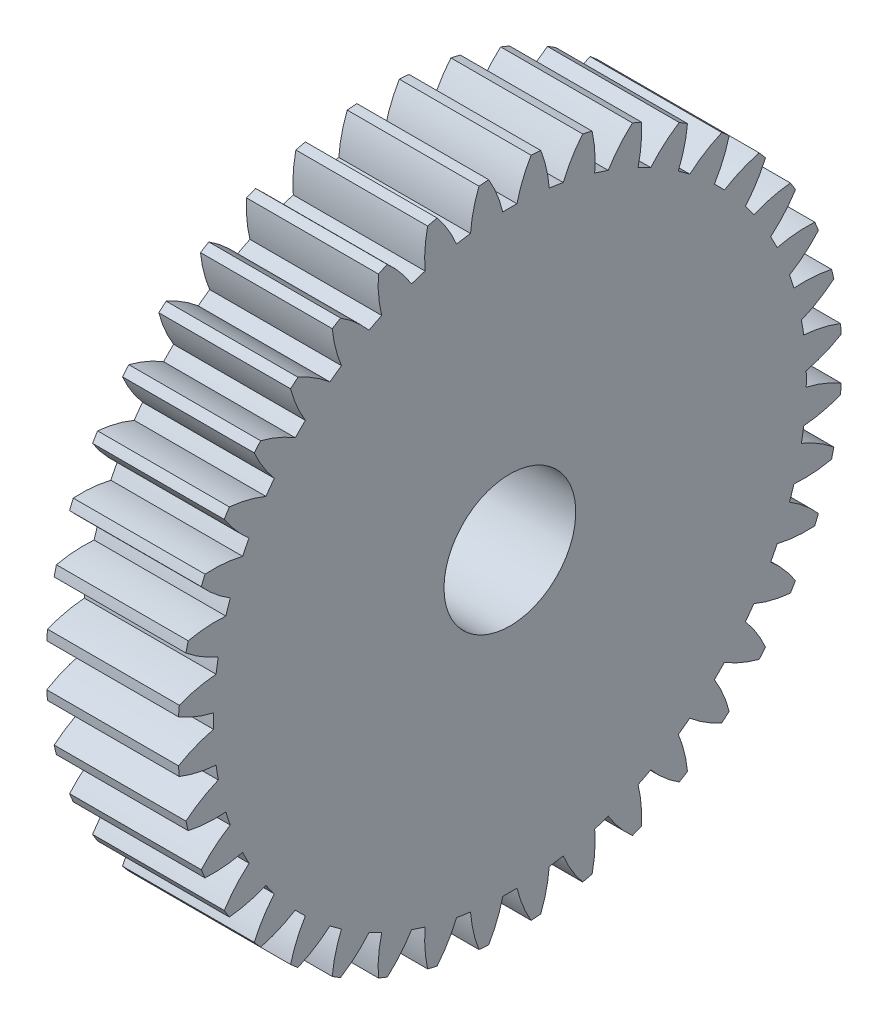
SolidWorks part; units mm, degrees
ref_plane "Plane1" through (0, 0, 0) normal (0, 0, 1) x (1, 0, 0)
ref_plane "Plane2" through (0, 0, 0) normal (0, 1, 0) x (1, 0, 0)
ref_plane "Plane3" through (0, 0, 0) normal (1, 0, 0) x (0, 0, -1)
sketch "HoldingSke" plane through (0, 0, 0) normal (0, 1, 0) x (1, 0, 0)
  line L0 (0, 0) -> (1.2767, -1.0713)
  line L1 (-15, 0) -> (100, 0) construction
  line L2 (0, 0) -> (-2.1039, 2.3779)
  line L3 (0, 0) -> (-11.863, 4.5341)
  line L4 (0, 0) -> (6.6156, 5.5511)
  line L5 (0, 0) -> (-46.8476, -17.4728)
  line L6 (0, 0) -> (-4.1448, -2.7965)
  line L7 (-2.1039, 2.3779) -> (8.6586, 51.2059)
  line L8 (-76.2, 54.61) -> (-76.1, 54.61)
  line L9 (-71.009, 38.7566) -> (-53.1078, 45.2721)
  line L10 (-76.2, 71.12) -> (104.1128, 71.12)
  line L11 (0, 0) -> (-5, 0)
  line L12 (-76.2, 101.6) -> (-76.177, 101.6)
  line L13 (24.9733, 27.94) -> (52.9518, 28.4284)
  line L14 (24.9733, 27.94) -> (24.9743, 27.94)
  line L15 (24.9733, 27.94) -> (100.4006, 29.5858)
  line L16 (-63.627, -0.6) -> (-12.827, -0.6)
  circle A0 centre (0, 0) radius 0.4
  circle A1 centre (0, 0) radius 11.249
  circle A2 centre (0, 0) radius 37.5
  circle A3 centre (0, 0) radius 0.4
  dimension "MHD" = 22.498
  dimension "Hub_dia" = 75
  dimension "Bore" = 0.8
  dimension "MBD" = 0.8
  dimension "Num_teeth" = 40
  dimension "Pitch" = 1.6667
  dimension "Overall_len" = 50
  dimension "Show_teeth" = 40
  dimension "Thickness" = 5
  dimension "OAL" = 50.0001
  dimension "T_dim" = 0.1
  dimension "Ap" = 20
  dimension "H" = 19.05
  dimension "Pitch_radius" = 180.3128
  dimension "Width" = 5
  dimension "Backlash" = 0.023
  dimension "Addendum_fac" = 1
  dimension "Dedendum_fac" = 1.25
  dimension "Clearance_fac" = 0.25
  dimension "Dedendum_add" = 0.001
  dimension "Module" = 0.6
sketch "BasProSke" plane through (0, 0, 0) normal (0, 1, 0) x (1, 0, 0)
  line L0 (-10, 0) -> (60, 0) construction
  line L1 (0, 0) -> (0, 12.6)
  line L2 (0, 0) -> (5, 0)
  line L3 (5, 0) -> (5, 12.6)
  line L4 (5, 12.6) -> (0, 12.6)
  dimension "Thickness" = 5
  dimension "Diameter" = 25.2
revolve "Base-Revolve" add sketch "BasProSke" angle 360 about L0
sketch "TooCutSke" plane through (0, 0, 0) normal (1, 0, 0) x (0, 0, -1)
  line L1 (0, 0) -> (0, 107) construction
  line L2 (0, 0) -> (-0.5114, 11.9891) construction
  line L3 (0, 0) -> (-1.8818, 23.9106) construction
  line L4 (-0.5114, 11.9891) -> (-0.9409, 11.9553) construction
  arc A0 (0.2694, 11.2458) -> (-0.2694, 11.2458) centre (0, 0) ccw
  arc A1 (0.8191, 12.5988) -> (-0.8191, 12.5988) centre (0, 0) ccw
  circle A2 centre (0, 0) radius 12 construction
  circle A3 centre (0, 0) radius 11.2763 construction
  arc A4 (-0.2694, 11.2458) -> (-0.8191, 12.5988) centre (-4.9396, 10.1368) ccw
  arc A5 (0.8191, 12.5988) -> (0.2694, 11.2458) centre (4.9396, 10.1368) ccw
  dimension "Root_dia" = 22.498
  dimension "Overcut_dia" = 25.2508
  dimension "Pitch_dia" = 24
  dimension "Base_dia" = 22.5526
  dimension "Flank_rad" = 4.8
  dimension "Half_ang" = 4.5
  dimension "Half_CT" = 0.4309
extrude "ToothCut" cut sketch "TooCutSke" along normal through all
fillet "Breaks" [suppressed] radius 0.012
fillet "RootFillets" [suppressed] radius 0.151
pattern_circular "TeethCuts" count 40 every 9 about axis through (-10, 0, 0) along (1, 0, 0) of "ToothCut", "RootFillets", "Breaks"
sketch "HubNeaOneSke" plane through (0, 0, 0) normal (-1, 0, 0) x (0, 0, 1)
  circle A0 centre (0, 0) radius 11.249
  dimension "Diameter" = 22.498
extrude "HubNearOne" [suppressed] add sketch "HubNeaOneSke" along normal blind 45.0001
sketch "HubNeaBotSke" plane through (0, 0, 0) normal (-1, 0, 0) x (0, 0, 1)
  circle A0 centre (0, 0) radius 11.249
  dimension "Diameter" = 22.498
extrude "HubNearBoth" [suppressed] add sketch "HubNeaBotSke" along normal blind 22.5
ref_plane "FarPln" through (5, 0, 0) normal (1, 0, 0) x (0, 0, -1)
sketch "HubFarSke" plane through (5, 0, 0) normal (1, 0, 0) x (0, 0, -1)
  circle A0 centre (0, 0) radius 11.249
  dimension "Diameter" = 22.498
extrude "HubFar" [suppressed] add sketch "HubFarSke" along normal blind 22.5
sketch "BorSke" plane through (0, 0, 0) normal (1, 0, 0) x (0, 0, -1)
  circle A0 centre (0, 0) radius 0.4
  dimension "Diameter" = 0.8
extrude "Bore" cut sketch "BorSke" along normal mid plane 100.0001
sketch "KeySke" plane through (0, 0, 0) normal (1, 0, 0) x (0, 0, -1)
  line L0 (-0.05, 0) -> (-0.05, 0.5)
  line L1 (-0.05, 0.5) -> (0.05, 0.5)
  line L2 (0.05, 0.5) -> (0.05, 0)
  line L3 (0, 0) -> (0, 34) construction
  line L4 (-0.05, 0) -> (0.05, 0)
  dimension "Offset" = 0.5
  dimension "Width" = 0.1
extrude "Keyway" [suppressed] cut sketch "KeySke" along normal mid plane 100.0001
pattern_circular "Keyway2" [suppressed] count 2 every 90 about axis through (-10, 0, 0) along (1, 0, 0)
sketch "Sketch1" plane through (0, 0, 0) normal (-1, 0, 0) x (0, 0, 1)
  circle A0 centre (0, 0) radius 2.5
  dimension "D1" = 5
extrude "Cut-Extrude1" cut sketch "Sketch1" against normal through all
equation "' \"Module@HoldingSke\" = 6.35"
equation "' \"Num_teeth@HoldingSke\" = 12"
equation "' \"Ap@HoldingSke\" =  20"
equation "' \"Ap@HoldingSke\" = 20"
equation "' \"Width@HoldingSke\" = 0.5 * 25.4"
equation "' \"Hub_dia@HoldingSke\"= 1 * 25.4"
equation "' \"Hub_dia@HoldingSke\" = 1 * 25.4"
equation "' \"Overall_len@HoldingSke\" = 1.0 * 25.4"
equation "' \"Bore@HoldingSke\" = 0.75 * 25.4"
equation "' \"T_dim@HoldingSke\" = 0.1 * 25.4"
equation "' \"Width@KeySke\" = 0.25 * 25.4"
equation "' \"Show_teeth@HoldingSke\" = 13"
equation "' \"Backlash@HoldingSke\" = 0.009 * 25.4"
equation "' \"Addendum_fac@HoldingSke\" = 1.0"
equation "' \"Dedendum_fac@HoldingSke\" = 1.25"
equation "' \"Dedendum_add@HoldingSke\" = 0.00005 * 25.4"
equation "' \"Clearance_fac@HoldingSke\" = 0.25"
equation "\"Pitch@HoldingSke\" = 1 / \"Module@HoldingSke\""
equation "\"Overcut_dia@TooCutSke\" = (\"Num_teeth@HoldingSke\" + 2 * \"Addendum_fac@HoldingSke\") / \"Pitch@HoldingSke\" + 0.002 * 25.4"
equation "\"Pitch_dia@TooCutSke\" = \"Num_teeth@HoldingSke\" / \"Pitch@HoldingSke\""
equation "\"Base_dia@TooCutSke\" = \"Num_teeth@HoldingSke\" / \"Pitch@HoldingSke\" * cos((\"Ap@HoldingSke\"  * 3.14159265 / 180))"
equation "\"Root_dia@TooCutSke\" = (\"Num_teeth@HoldingSke\" + 2) / \"Pitch@HoldingSke\" - 2 * (\"Addendum_fac@HoldingSke\" + \"Dedendum_fac@HoldingSke\") / \"Pitch@HoldingSke\" - \"Dedendum_add@HoldingSke\" * 2"
equation "\"Half_ang@TooCutSke\" = 180 / \"Num_teeth@HoldingSke\""
equation "\"Half_CT@TooCutSke\" = \"Num_teeth@HoldingSke\" / \"Pitch@HoldingSke\" * sin((3.14159265 / 2 / \"Num_teeth@HoldingSke\")) / 2 - 7 * \"Backlash@HoldingSke\" / 4"
equation "\"Flank_rad@TooCutSke\" = \"Num_teeth@HoldingSke\" / \"Pitch@HoldingSke\" / 5"
equation "\"Radius@RootFillets\" = \"Clearance_fac@HoldingSke\" / \"Pitch@HoldingSke\" + \"Dedendum_add@HoldingSke\""
equation "\"Break_rad@Breaks\" = 0.02 / \"Pitch@HoldingSke\""
equation "\"Thickness@HoldingSke\" = \"Width@HoldingSke\""
equation "\"OAL@HoldingSke\" = \"Thickness@HoldingSke\""
equation "\"MHD@HoldingSke\" = (\"Num_teeth@HoldingSke\" + 2) / \"Pitch@HoldingSke\" - 2 * (\"Addendum_fac@HoldingSke\" + \"Dedendum_fac@HoldingSke\")  / \"Pitch@HoldingSke\" - \"Dedendum_add@HoldingSke\" * 2"
equation "\"MBD@HoldingSke\" = (\"Num_teeth@HoldingSke\" + 2) / \"Pitch@HoldingSke\" - 2 * (\"Addendum_fac@HoldingSke\" + \"Dedendum_fac@HoldingSke\")  / \"Pitch@HoldingSke\" - \"Dedendum_add@HoldingSke\" * 2 - 0.002 * 25.4"
equation "\"MHD@HoldingSke\" = ((sgn( \"MHD@HoldingSke\" - \"Hub_dia@HoldingSke\" )-1)*( \"MHD@HoldingSke\" - \"Hub_dia@HoldingSke\" ))/-2+ \"Hub_dia@HoldingSke\""
equation "\"MBD@HoldingSke\" = ((sgn( \"MBD@HoldingSke\" - \"Bore@HoldingSke\" )-1)*( \"MBD@HoldingSke\" - \"Bore@HoldingSke\" ))/-2+ \"Bore@HoldingSke\""
equation "\"OAL@HoldingSke\" = ((sgn( \"OAL@HoldingSke\" - \"Overall_len@HoldingSke\" )+1)*( \"OAL@HoldingSke\" - \"Overall_len@HoldingSke\" ))/2 + \"Overall_len@HoldingSke\" + 0.000002 * 25.4"
equation "\"Num_teeth@TeethCuts\" = int( \"Show_teeth@HoldingSke\" ) + 1"
equation "\"Num_teeth@TeethCuts\" = ((sgn( \"Num_teeth@TeethCuts\" - \"Num_teeth@HoldingSke\" )-1)*( \"Num_teeth@TeethCuts\" - \"Num_teeth@HoldingSke\" ))/-2+ \"Num_teeth@HoldingSke\""
equation "\"Num_teeth@TeethCuts\" = ((sgn( \"Num_teeth@TeethCuts\" - 2.0)+1)*( \"Num_teeth@TeethCuts\" - 2.0))/2 +2.0"
equation "\"Angle@TeethCuts\" = 360.0 / \"Num_teeth@HoldingSke\""
equation "\"Diameter@BasProSke\" = (\"Num_teeth@HoldingSke\" + 2 * \"Addendum_fac@HoldingSke\") / \"Pitch@HoldingSke\""
equation "\"Thickness@BasProSke\"  = \"Thickness@HoldingSke\""
equation "' \"Fillet_rad@BasProSke\" =  \"Thickness@HoldingSke\" * 0.05"
equation "' \"Fillet_rad@BasProSke\" = \"Thickness@HoldingSke\" * 0.05"
equation "\"MHD@HoldingSke\" = ((sgn( \"MHD@HoldingSke\" - \"Root_dia@TooCutSke\" )-1)*( \"MHD@HoldingSke\" - \"Root_dia@TooCutSke\" ))/-2+ \"Root_dia@TooCutSke\""
equation "\"Diameter@HubNeaOneSke\" = \"MHD@HoldingSke\""
equation "\"Length@HubNearOne\" = \"OAL@HoldingSke\" - \"Thickness@BasProSke\""
equation "\"Diameter@HubNeaBotSke\" = \"MHD@HoldingSke\""
equation "\"Length@HubNearBoth\" = ( \"OAL@HoldingSke\" - \"Thickness@BasProSke\" ) / 2.0"
equation "\"Thickness@FarPln\" = \"Thickness@BasProSke\""
equation "\"Diameter@HubFarSke\" = \"MHD@HoldingSke\""
equation "\"Length@HubFar\" = ( \"OAL@HoldingSke\" - \"Thickness@BasProSke\" ) / 2.0"
equation "\"Diameter@BorSke\" = \"MBD@HoldingSke\""
equation "\"D1@Bore\" = \"OAL@HoldingSke\" * 2.0"
equation "\"D1@Keyway\" = \"OAL@HoldingSke\" * 2.0"
equation "\"Offset@KeySke\" = \"T_dim@HoldingSke\" + \"MBD@HoldingSke\" / 2.0"
